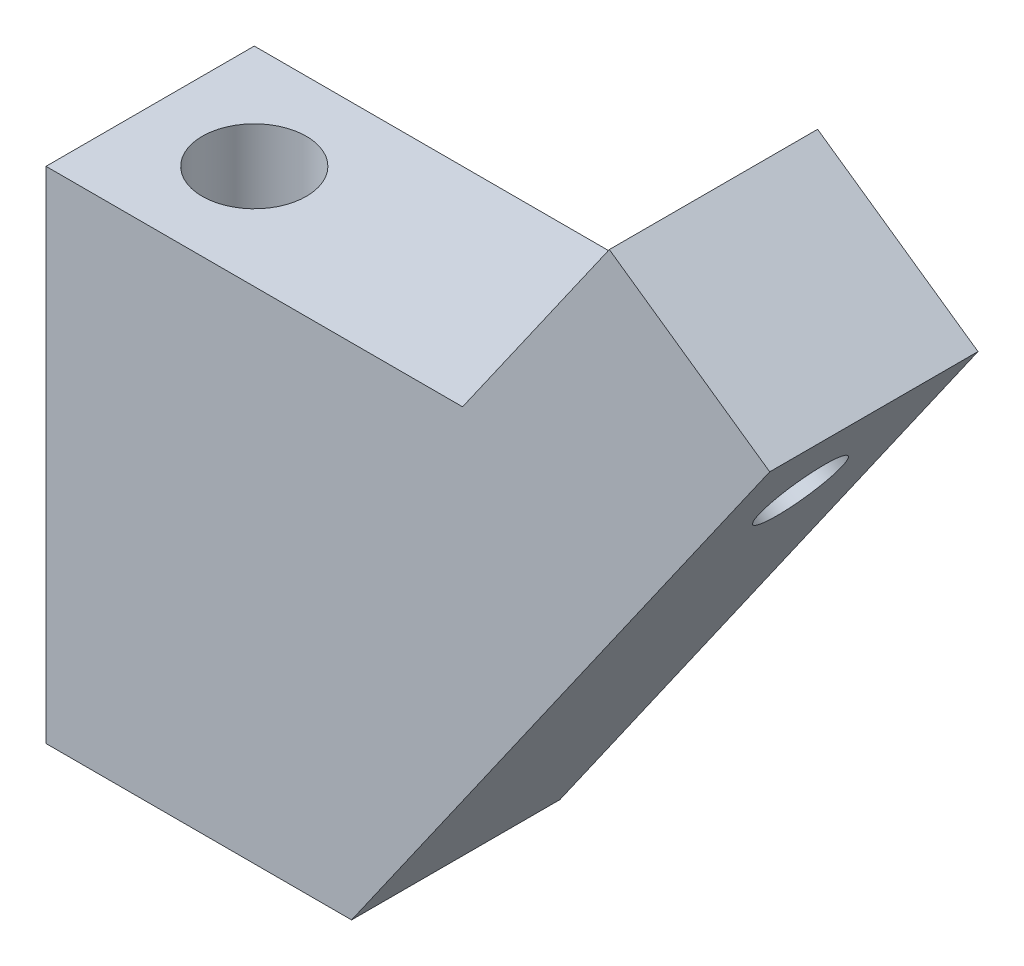
SolidWorks part; units mm, degrees
ref_plane "Front Plane" through (0, 0, 0) normal (0, 0, 1) x (1, 0, 0)
ref_plane "Top Plane" through (0, 0, 0) normal (0, 1, 0) x (1, 0, 0)
ref_plane "Right Plane" through (0, 0, 0) normal (1, 0, 0) x (0, 0, -1)
sketch "Sketch1" plane through (0, 0, 0) normal (0, 0, 1) x (1, 0, 0)
  line L0 (25.4, 30.48) -> (34.3477, 43.2587)
  line L1 (0, 30.48) -> (25.4, 30.48)
  line L2 (0, 30.48) -> (0, 0)
  line L3 (0, 0) -> (18.6313, 0)
  line L5 (34.3477, 43.2587) -> (44.1268, 36.4113)
  line L6 (44.1268, 36.4113) -> (18.6313, 0)
  dimension "D1" = 30.48
  dimension "D2" = 25.4
  dimension "D3" = 11.938
  dimension "D4" = 125
  dimension "D5" = 44.45
extrude "Boss-Extrude2" add sketch "Sketch1" along normal blind 12.7 contours L1 L0 L5 L6 L3 L2
sketch "Sketch2" plane through (2.7227, -1.9065, 0) normal (-0.8192, 0.5736, 0) x (0, 0, 1)
  line L0 (0, 47.3365) -> (12.7, 47.3365) construction
  line L2 (0, 39.5366) -> (0, 55.1365) construction
  line L3 (12.7, 39.5366) -> (12.7, 55.1365) construction
  line L4 (6.35, 55.1365) -> (6.35, 39.5366) construction
  line L5 (12.7, 55.1365) -> (0, 55.1365) construction
  line L6 (12.7, 39.5366) -> (0, 39.5366) construction
  circle A0 centre (6.35, 47.3365) radius 2.54
  dimension "D1" = 5.08
extrude "Cut-Extrude1" cut sketch "Sketch2" against normal up to surface (11.938 mm away) up to face at (31.379, 18.2057, 6.35)
sketch "Sketch3" plane through (0, 30.48, 0) normal (0, 1, 0) x (1, 0, 0)
  line L0 (0, -6.35) -> (25.4, -6.35) construction
  line L1 (0, -12.7) -> (0, 0) construction
  line L2 (25.4, -12.7) -> (25.4, 0) construction
  circle A0 centre (6.35, -6.35) radius 3.175
  dimension "D1" = 6.35
  dimension "D2" = 6.35
extrude "Cut-Extrude4" cut sketch "Sketch3" against normal up to surface (30.48 mm away) up to face at (9.3156, 0, 6.35)
